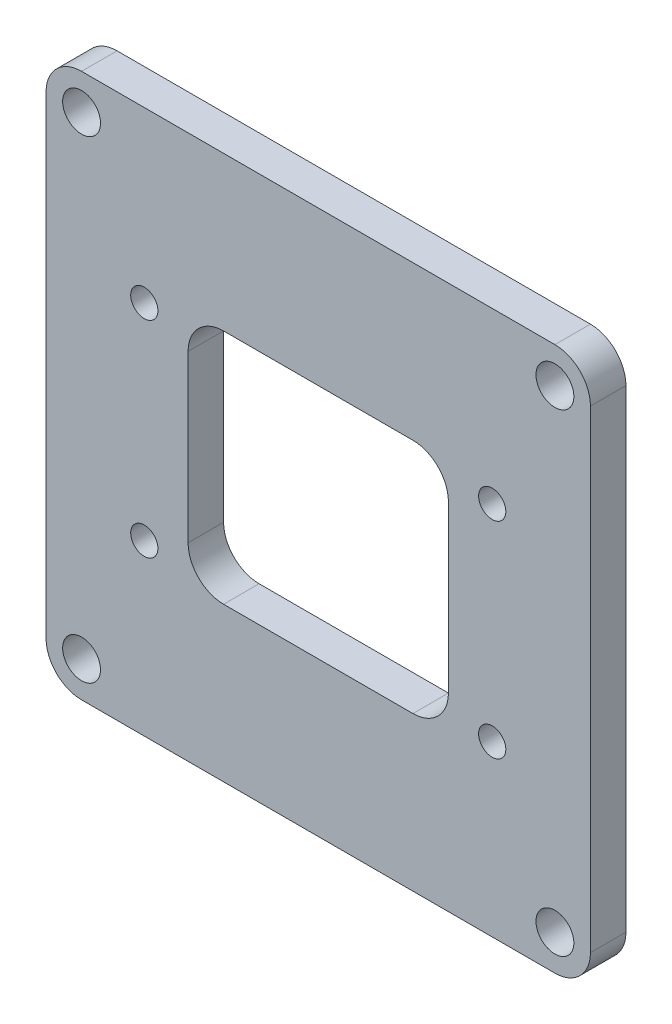
SolidWorks part; units mm, degrees
material "Thornel Mat VMA"
ref_plane "前视基准面" through (0, 0, 0) normal (0, 0, 1) x (1, 0, 0)
ref_plane "上视基准面" through (0, 0, 0) normal (0, 1, 0) x (1, 0, 0)
ref_plane "右视基准面" through (0, 0, 0) normal (1, 0, 0) x (0, 0, -1)
other "Configuration Table"
sketch "草图1" plane through (0, 0, 0) normal (0, 0, 1) x (1, 0, 0)
  line L1 (23, -23) -> (-23, -23)
  line L2 (23, -23) -> (23, 23)
  line L3 (23, 23) -> (-23, 23)
  line L4 (-23, -23) -> (-23, 23)
  line L5 (23, -23) -> (-23, 23) construction
  line L6 (23, 23) -> (-23, -23) construction
  line L7 (20, -20) -> (-20, -20) construction
  line L8 (20, -20) -> (20, 20) construction
  line L9 (20, 20) -> (-20, 20) construction
  line L10 (-20, -20) -> (-20, 20) construction
  line L11 (20, -20) -> (-20, 20) construction
  line L12 (20, 20) -> (-20, -20) construction
  line L13 (14.7, -8.7) -> (-14.7, -8.7) construction
  line L14 (14.7, -8.7) -> (14.7, 8.7) construction
  line L15 (14.7, 8.7) -> (-14.7, 8.7) construction
  line L16 (-14.7, -8.7) -> (-14.7, 8.7) construction
  line L17 (14.7, -8.7) -> (-14.7, 8.7) construction
  line L18 (14.7, 8.7) -> (-14.7, -8.7) construction
  circle A0 centre (-20, 20) radius 1.6
  circle A1 centre (20, 20) radius 1.6
  circle A2 centre (20, -20) radius 1.6
  circle A3 centre (-20, -20) radius 1.6
  circle A4 centre (-14.7, 8.7) radius 1.15
  circle A5 centre (14.7, 8.7) radius 1.15
  circle A6 centre (14.7, -8.7) radius 1.15
  circle A7 centre (-14.7, -8.7) radius 1.15
  point P0 (0, 0)
  point P6 (0, 0)
  point P15 (0, 0)
  dimension "D5" = 3.2
  dimension "D8" = 2.3
  dimension "D1" = 46
  dimension "D2" = 46
  dimension "D3" = 40
  dimension "D4" = 40
  dimension "D6" = 17.4
  dimension "D7" = 29.4
extrude "凸台-拉伸1" add sketch "草图1" along normal blind 3
fillet "圆角1" radius 3 4 edges at (23, 23, 1.5) (23, -23, 1.5) (-23, -23, 1.5) (-23, 23, 1.5)
sketch "草图2" plane through (0, 0, 3) normal (0, 0, 1) x (1, 0, 0)
  line L0 (20, 23) -> (-20, 23) construction
  line L1 (11, -10) -> (-11, -10)
  line L2 (11, -10) -> (11, 10)
  line L3 (11, 10) -> (-11, 10)
  line L4 (-11, -10) -> (-11, 10)
  line L5 (11, -10) -> (-11, 10) construction
  line L6 (11, 10) -> (-11, -10) construction
  line L7 (23, -20) -> (23, 20) construction
  point P0 (0, 0)
  dimension "D1" = 13
  dimension "D2" = 12
extrude "切除-拉伸1" cut sketch "草图2" against normal blind 3
fillet "圆角2" radius 3 4 edges at (11, 10, 1.5) (11, -10, 1.5) (-11, -10, 1.5) (-11, 10, 1.5)
